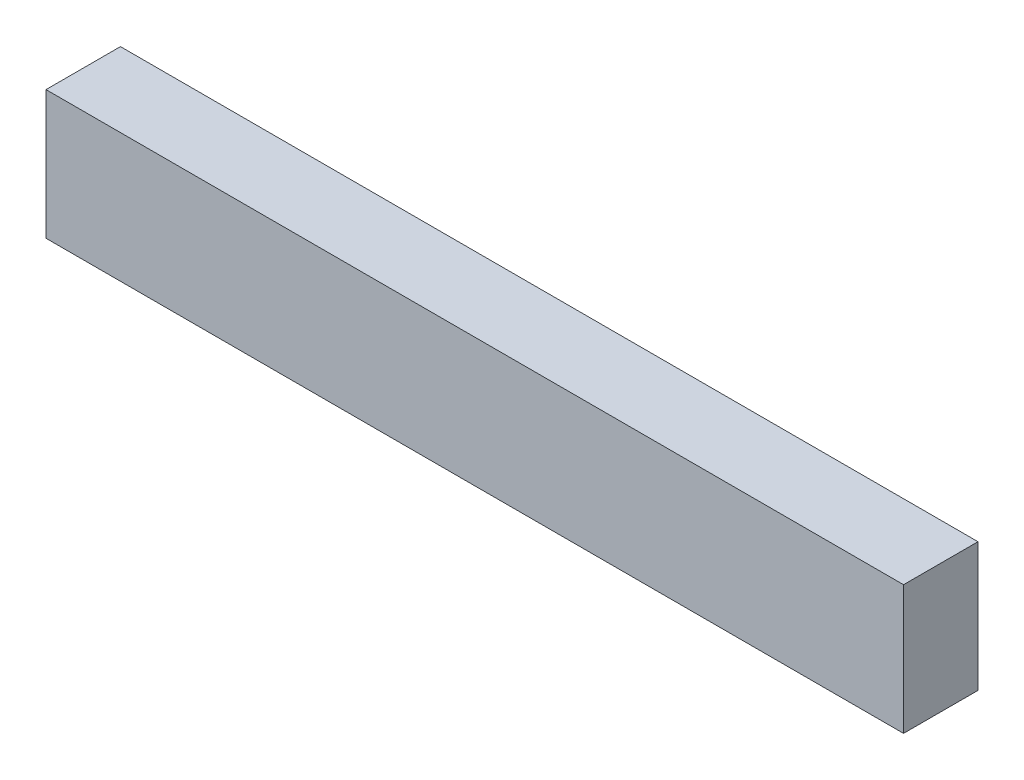
SolidWorks part; units mm, degrees
ref_plane "Front Plane" through (0, 0, 0) normal (0, 0, 1) x (1, 0, 0)
ref_plane "Top Plane" through (0, 0, 0) normal (0, 1, 0) x (1, 0, 0)
ref_plane "Right Plane" through (0, 0, 0) normal (1, 0, 0) x (0, 0, -1)
sketch "Sketch1" plane through (0, 0, 0) normal (0, 0, 1) x (1, 0, 0)
  line L0 (-79.2368, 62.27) -> (4.6645, 62.27) construction
  line L1 (-79.0368, 62.07) -> (4.4645, 62.07)
  line L2 (-79.0368, 62.07) -> (-79.0368, 49.53)
  line L3 (-79.0368, 49.53) -> (4.4645, 49.53)
  line L4 (4.4645, 62.07) -> (4.4645, 49.53)
  line L5 (4.6645, 62.27) -> (4.6645, 49.33) construction
  line L6 (4.6645, 49.33) -> (-79.2368, 49.33) construction
  line L7 (-79.2368, 62.27) -> (-79.2368, 49.33) construction
  dimension "D1" = 0.2
  dimension "D2" = 0.2
  dimension "D3" = 0.2
  dimension "D4" = 0.2
extrude "Boss-Extrude1" add sketch "Sketch1" along normal blind 7.25
shell "Shell1" thickness 0.5
equation "\"D2@Sketch1\"=\"D1@Sketch1\""
equation "\"D3@Sketch1\"=\"D1@Sketch1\""
equation "\"D4@Sketch1\"=\"D1@Sketch1\""
